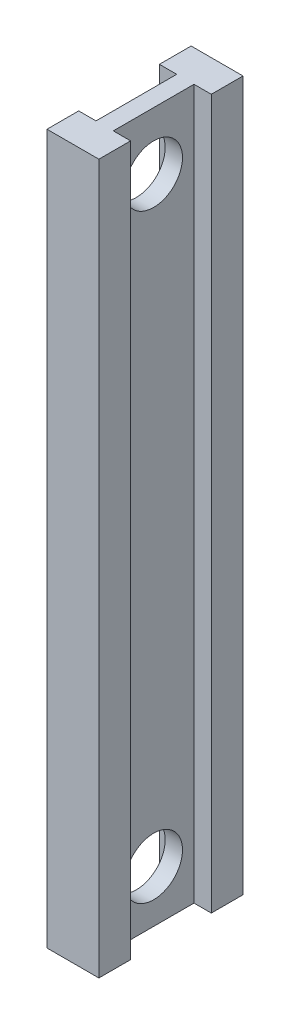
SolidWorks part; units mm, degrees
material "PE High Density"
ref_plane "Front Plane" through (0, 0, 0) normal (0, 0, 1) x (1, 0, 0)
ref_plane "Top Plane" through (0, 0, 0) normal (0, 1, 0) x (1, 0, 0)
ref_plane "Right Plane" through (0, 0, 0) normal (1, 0, 0) x (0, 0, -1)
sketch "Sketch1" plane through (0, 0, 0) normal (0, 1, 0) x (1, 0, 0)
  line L0 (-45, -70) -> (-45, -125)
  line L1 (-45, 125) -> (45, 125)
  line L2 (-45, 125) -> (-45, 70)
  line L3 (-45, -125) -> (45, -125)
  line L4 (45, 125) -> (45, 70)
  line L5 (-45, 125) -> (45, -125) construction
  line L6 (-45, -125) -> (45, 125) construction
  line L7 (-45, 70) -> (-15, 70)
  line L9 (-45, -70) -> (-15, -70)
  line L10 (-15, 70) -> (-15, -70)
  line L11 (45, 70) -> (15, 70)
  line L13 (45, -70) -> (15, -70)
  line L14 (15, 70) -> (15, -70)
  line L15 (45, -70) -> (45, -125)
  point P0 (0, 0)
  point P14 (30, 70)
  dimension "D1" = 90
  dimension "D2" = 250
  dimension "D3" = 30
  dimension "D4" = 55
  dimension "D5" = 55
  dimension "D6" = 30
extrude "Boss-Extrude1" add sketch "Sketch1" along normal blind 1230
sketch "Sketch2" plane through (15, 0, 0) normal (1, 0, 0) x (0, 0, -1)
  line L0 (-70, 0) -> (70, 0) construction
  circle A0 centre (0, 90) radius 50
  dimension "D1" = 100
  dimension "D2" = 90
extrude "Cut-Extrude1" cut sketch "Sketch2" against normal blind 1200
sketch "Sketch3" plane through (15, 0, 0) normal (1, 0, 0) x (0, 0, -1)
  line L0 (-70, 1230) -> (70, 1230) construction
  circle A0 centre (0, 1130) radius 50
  dimension "D1" = 100
  dimension "D2" = 100
extrude "Cut-Extrude2" cut sketch "Sketch3" against normal blind 1200
scale "Scale1" scale about centroid uniform scaling yes scale factor 0.75
